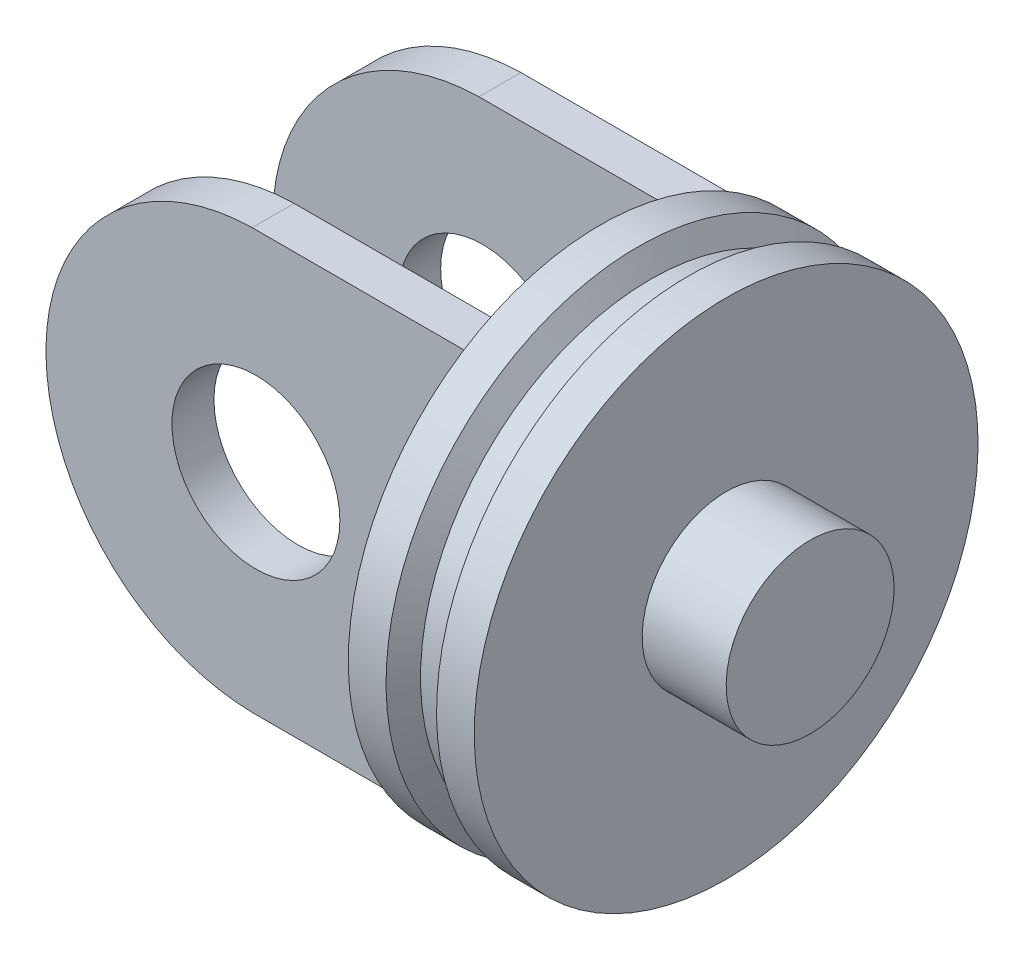
SolidWorks part; units mm, degrees
material "6061-T4 (SS)"
ref_plane "Alzado" through (0, 0, 0) normal (0, 0, 1) x (1, 0, 0)
ref_plane "Planta" through (0, 0, 0) normal (0, 1, 0) x (1, 0, 0)
ref_plane "Vista lateral" through (0, 0, 0) normal (1, 0, 0) x (0, 0, -1)
sketch "Croquis1" plane through (0, 0, 0) normal (0, 0, 1) x (1, 0, 0)
  line L0 (0, 0) -> (3.75, 0)
  line L1 (-3.75, -15) -> (3.75, -15)
  line L2 (-3.75, -15) -> (-3.75, 15)
  line L3 (-3.75, 15) -> (3.75, 15)
  line L4 (3.75, -15) -> (3.75, 15)
  line L5 (-3.75, -15) -> (3.75, 15) construction
  line L6 (-3.75, 15) -> (3.75, -15) construction
  line L7 (3.75, 0) -> (-3.75, 0)
  line L8 (-3.75, 0) -> (-3.75, 5)
  line L9 (-3.75, 5) -> (3.75, 5)
  line L10 (3.75, 5) -> (3.75, 0)
  line L11 (3.75, 5) -> (8.75, 5)
  line L12 (8.75, 5) -> (8.75, 0)
  line L13 (8.75, 0) -> (3.75, 0)
  line L14 (-10.1044, 0) -> (10.3569, 0) construction
  line L15 (-1.5, 4.385) -> (1.5037, 4.385)
  line L16 (-1.5, 4.385) -> (-1.5, 15)
  line L17 (-1.5, 15) -> (1.5037, 15)
  line L18 (1.5037, 4.385) -> (1.5037, 15)
  line L19 (-1.5, 4.385) -> (1.5037, 15) construction
  line L20 (-1.5, 15) -> (1.5037, 4.385) construction
  line L21 (1.5037, 15) -> (0.7518, 16.3022)
  line L22 (0.7518, 16.3022) -> (-0.7518, 16.3022)
  line L23 (-0.7518, 16.3022) -> (-1.5037, 15)
  line L24 (-1.5037, 15) -> (-0.7518, 13.6978)
  line L25 (-0.7518, 13.6978) -> (0.7518, 13.6978)
  line L26 (0.7518, 13.6978) -> (1.5037, 15)
  circle A0 centre (0, 15) radius 1.3022 construction
  point P0 (0, 0)
  point P8 (0.0018, 9.6925)
  dimension "D1" = 30
  dimension "D2" = 5
  dimension "D3" = 5
  dimension "D4" = 2.2463
  dimension "D5" = 7.5
  dimension "D6" = 2.25
revolve "Revolución1" add sketch "Croquis1" angle 360 about L14
sketch "Croquis2" plane through (-3.75, 0, 0) normal (-1, 0, 0) x (0, 0, 1)
  line L0 (0, 15) -> (0, -15)
  line L1 (-15, -15) -> (15, -15)
  line L2 (-15, -15) -> (-15, 15)
  line L3 (-15, 15) -> (15, 15)
  line L4 (15, -15) -> (15, 15)
  line L5 (-15, -15) -> (15, 15) construction
  line L6 (-15, 15) -> (15, -15) construction
  line L8 (-8, -12.5) -> (-5.5, -12.5)
  line L9 (-8, -12.5) -> (-8, 12.5)
  line L10 (-8, 12.5) -> (-5.5, 12.5)
  line L11 (-5.5, -12.5) -> (-5.5, 12.5)
  line L12 (-8, -12.5) -> (-5.5, 12.5) construction
  line L13 (-8, 12.5) -> (-5.5, -12.5) construction
  line L14 (8, -12.5) -> (5.5, -12.5)
  line L15 (8, -12.5) -> (8, 12.5)
  line L16 (8, 12.5) -> (5.5, 12.5)
  line L17 (5.5, -12.5) -> (5.5, 12.5)
  line L18 (8, -12.5) -> (5.5, 12.5) construction
  line L19 (8, 12.5) -> (5.5, -12.5) construction
  point P0 (0, 0)
  point P8 (-6.75, 0)
  point P13 (6.75, 0)
  dimension "D1" = 5.5
  dimension "D2" = 2.5
  dimension "D3" = 5.5
  dimension "D4" = 2.5
  dimension "D5" = 25
  dimension "D6" = 0
  dimension "D7" = 25
  dimension "D8" = 0
extrude "Saliente-Extruir1" add sketch "Croquis2" along normal blind 25 contours L8 L11 L10 L9 | L17 L14 L15 L16
sketch "Croquis3" plane through (0, 0, 8) normal (0, 0, 1) x (1, 0, 0)
  line L1 (-28.75, -12.5) -> (-28.75, 12.5) construction
  line L2 (-28.7519, 0) -> (-28.75, 12.5)
  line L3 (-28.75, 12.5) -> (-16.25, 12.5019)
  line L4 (-16.25, 12.5019) -> (-16.25, -12.5019)
  line L5 (-16.25, -12.5019) -> (-28.75, -12.5)
  line L6 (-28.75, -12.5) -> (-28.7519, 0)
  circle A0 centre (-16.25, 0) radius 12.5019
  circle A1 centre (-16.25, 0) radius 5
  line M3 (-3.75, 12.5) -> (-28.75, 12.5)
  line M4 (-28.75, 12.5) -> (-28.75, -12.5)
  line M5 (-28.75, -12.5) -> (-3.75, -12.5)
  dimension "D1" = 12.5
extrude "Cortar-Extruir1" cut sketch "Croquis3" against normal blind 25 contours A0 M3 M4 | A0 M4 M5 | L4 A1 | L4 A1
